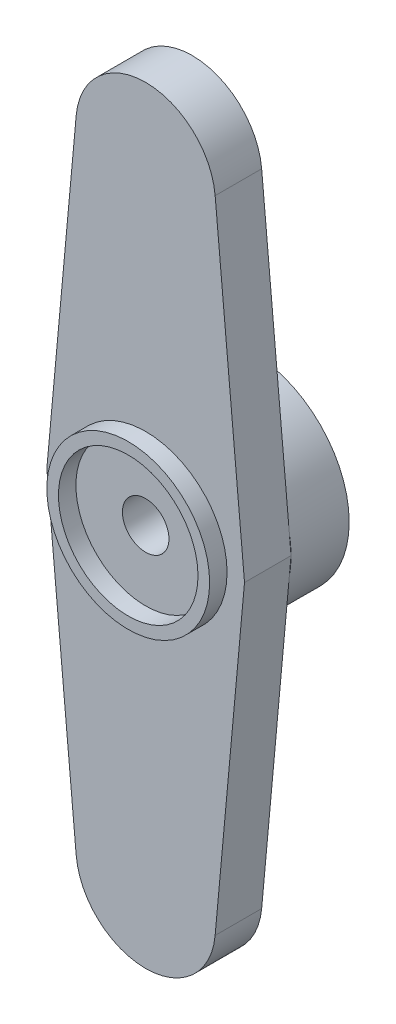
SolidWorks part; units mm, degrees
ref_plane "Front Plane" through (0, 0, 0) normal (1, 0, 0) x (0, 1, 0)
ref_plane "Top Plane" through (0, 0, 0) normal (0, 0, 1) x (0, 1, 0)
ref_plane "Right Plane" through (0, 0, 0) normal (0, 1, 0) x (-1, 0, 0)
sketch "Sketch1" plane through (0, 0, 0) normal (0, 0, 1) x (0, 1, 0)
  circle A0 centre (0, 0) radius 2.5
  circle A1 centre (0, 0) radius 4.25
  dimension "D1" = 5
  dimension "D2" = 8.5
extrude "Boss-Extrude1" add sketch "Sketch1" along normal blind 2.5
sketch "Sketch2" plane through (0, 0, 2.5) normal (0, 0, 1) x (1, 0, 0)
  line L0 (-4.25, 0) -> (-2.9875, 13.7738)
  line L1 (2.9875, 13.7738) -> (4.25, 0)
  line L2 (0, 0) -> (-50000, 0) construction
  line L3 (2.9875, -13.7738) -> (4.25, 0)
  line L4 (-4.25, 0) -> (-2.9875, -13.7738)
  circle A0 centre (0, 0) radius 4.25 construction
  arc A1 (-2.9875, 13.7738) -> (2.9875, 13.7738) centre (0, 13.5) cw
  circle A2 centre (0, 0) radius 4.25 construction
  arc A3 (-2.9875, -13.7738) -> (2.9875, -13.7738) centre (0, -13.5) ccw
  circle A4 centre (0, 0) radius 1
  point P14 (0, 16.5)
  dimension "D1" = 16.5
  dimension "D2" = 3
  dimension "D3" = 2
extrude "Boss-Extrude2" add sketch "Sketch2" along normal blind 2
sketch "Sketch3" plane through (0, 0, 4.5) normal (0, 0, 1) x (1, 0, 0)
  circle A0 centre (0, 0) radius 3.5
  circle A1 centre (0, 0) radius 3
  dimension "D1" = 0.5
  dimension "D2" = 7
extrude "Boss-Extrude3" add sketch "Sketch3" along normal blind 0.75
